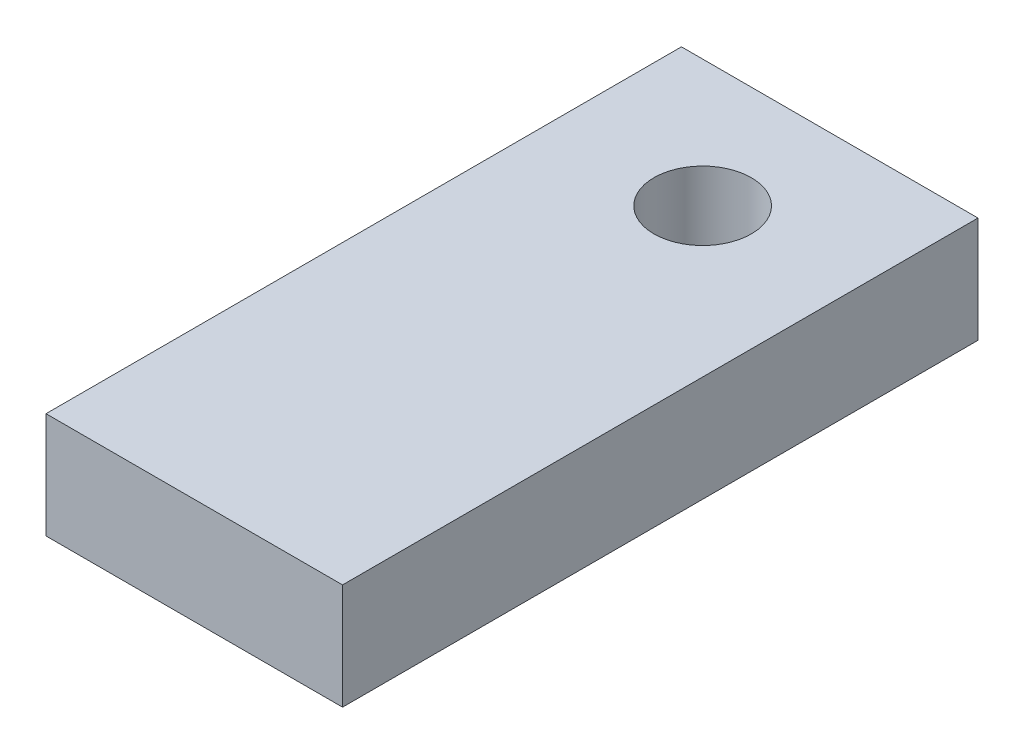
SolidWorks part; units mm, degrees
ref_plane "Front Plane" through (0, 0, 0) normal (0, 0, 1) x (1, 0, 0)
ref_plane "Top Plane" through (0, 0, 0) normal (0, 1, 0) x (1, 0, 0)
ref_plane "Right Plane" through (0, 0, 0) normal (1, 0, 0) x (0, 0, -1)
sketch "Sketch1" plane through (0, 0, 0) normal (0, 1, 0) x (1, 0, 0)
  line L1 (0, 0) -> (8.89, 0)
  line L2 (0, 0) -> (0, 19.05)
  line L3 (0, 19.05) -> (8.89, 19.05)
  line L4 (8.89, 0) -> (8.89, 19.05)
  circle A0 centre (4.445, 15.24) radius 1.4605
  dimension "D3" = 2.921
  dimension "D1" = 8.89
  dimension "D2" = 19.05
  dimension "D4" = 3.81
  dimension "D5" = 4.445
extrude "Boss-Extrude1" add sketch "Sketch1" along normal blind 3.175
